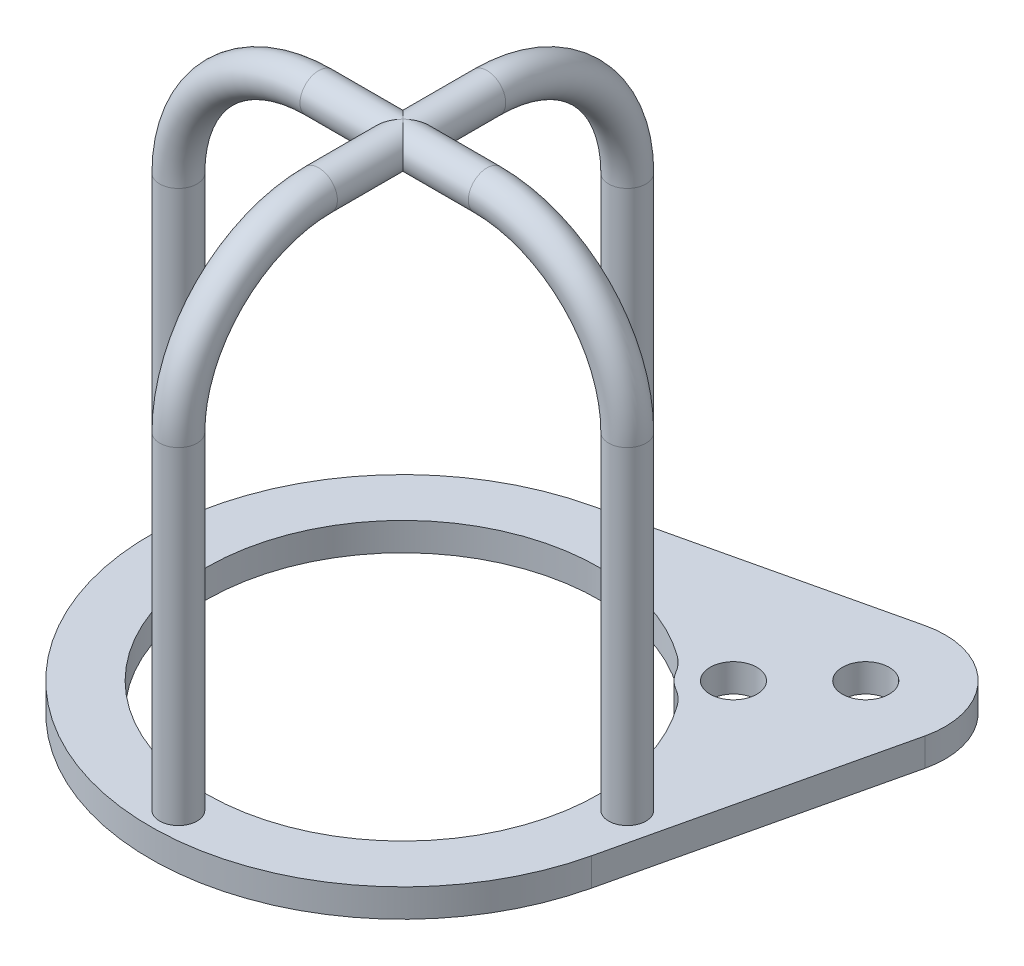
SolidWorks part; units mm, degrees
ref_plane "Plan de face" through (0, 0, 0) normal (0, 0, 1) x (1, 0, 0)
ref_plane "Plan de dessus" through (0, 0, 0) normal (0, 1, 0) x (1, 0, 0)
ref_plane "Plan de droite" through (0, 0, 0) normal (1, 0, 0) x (0, 0, -1)
sketch "Esquisse1" plane through (0, 0, 0) normal (0, 0, 1) x (1, 0, 0)
  line L0 (0, 50) -> (9, 50)
  line L1 (24, 35) -> (24, 0)
  line L2 (0, 0) -> (0, 50) construction
  line L3 (0, 0) -> (24, 0) construction
  arc A0 (24, 35) -> (9, 50) centre (9, 35) ccw
  dimension "D1" = 15
  dimension "D2" = 24
  dimension "D3" = 50
sketch "Esquisse2" plane through (0, 0, 0) normal (0, 1, 0) x (1, 0, 0)
  line L0 (9, 0) -> (24, 0) construction
  line L1 (0, 0) -> (24, 0) construction
  circle A0 centre (24, 0) radius 2
  dimension "D1" = 4
  dimension "D2" = 24
sweep "Balayage1" add profiles "Esquisse2" path "Esquisse1"
sketch "Esquisse3" plane through (0, 0, 0) normal (0, 0, 1) x (1, 0, 0)
  line L0 (0, 0) -> (0, 50) construction
  line L1 (0, 52) -> (0, 48) construction
pattern_circular "Répétition circulaire1" count 4 over 360 about axis through (0, 0, 0) along (0, 1, 0) of "Balayage1"
sketch "Esquisse4" plane through (0, 0, 0) normal (0, -1, 0) x (1, 0, 0)
  line L0 (0, 0) -> (33.2746, -33.2746) construction
  line L1 (0, 0) -> (0, -27) construction
  line L2 (26.2983, 6.1155) -> (33.0278, -22.8235)
  line L3 (22.8235, -33.0278) -> (-6.1155, -26.2983)
  circle A0 centre (0, 0) radius 21 construction
  circle A1 centre (0, 0) radius 27 construction
  circle A2 centre (17.6777, -17.6777) radius 2.5
  circle A3 centre (24.7487, -24.7487) radius 2.5
  arc A4 (33.0278, -22.8235) -> (22.8235, -33.0278) centre (24.7487, -24.7487) cw
  arc A5 (13.4545, -16.1238) -> (16.1238, -13.4545) centre (17.6777, -17.6777) cw
  arc A6 (16.1238, -13.4545) -> (13.4545, -16.1238) centre (0, 0) ccw
  arc A7 (26.2983, 6.1155) -> (-6.1155, -26.2983) centre (0, 0) ccw
  dimension "D1" = 42
  dimension "D2" = 6
  dimension "D3" = 45
  dimension "D6" = 5
  dimension "D7" = 6
  dimension "D8" = 2
  dimension "D4" = 25
  dimension "D5" = 10
extrude "Boss.-Extru.1" add sketch "Esquisse4" along normal blind 3
fillet "Congé1" radius 5 2 edges at (13.4545, -1.5, -16.1238) (16.1238, -1.5, -13.4545)
